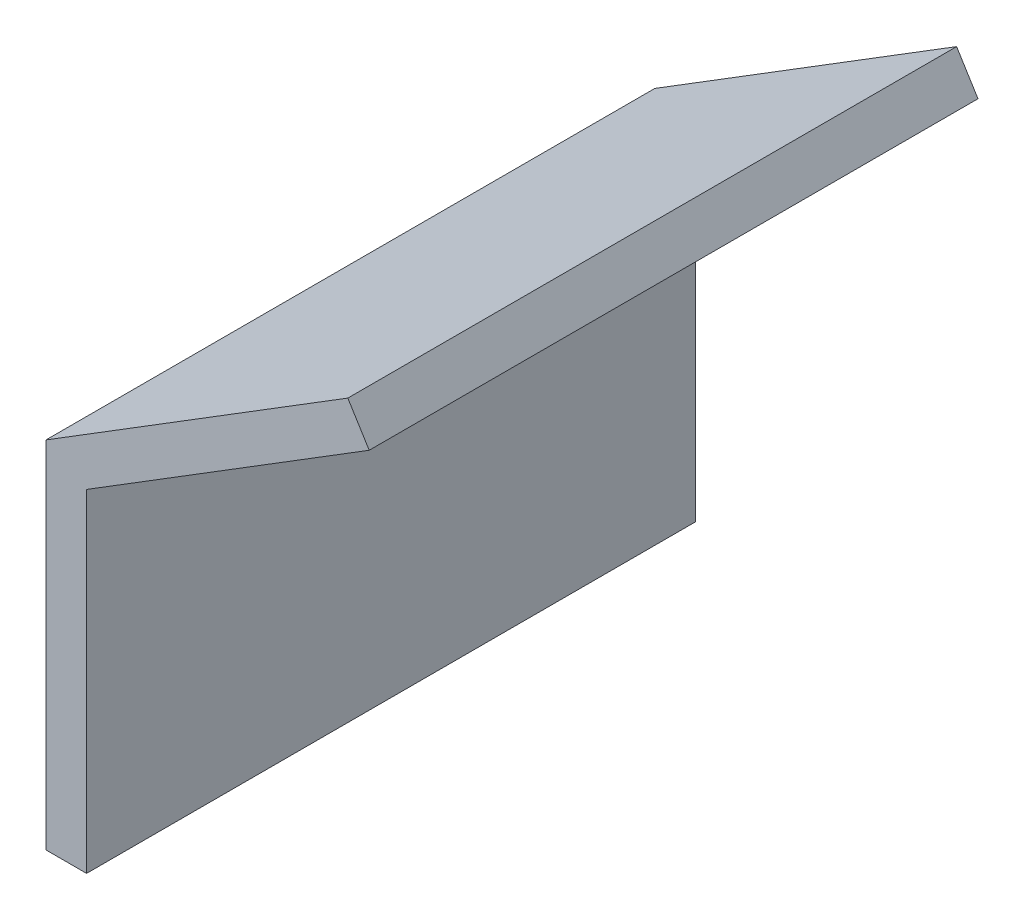
SolidWorks part; units mm, degrees
material "PLA"
ref_plane "Front Plane" through (0, 0, 0) normal (0, 0, 1) x (1, 0, 0)
ref_plane "Top Plane" through (0, 0, 0) normal (0, 1, 0) x (1, 0, 0)
ref_plane "Right Plane" through (0, 0, 0) normal (1, 0, 0) x (0, 0, -1)
sketch "Sketch1" plane through (0, 0, 0) normal (0, 0, 1) x (1, 0, 0)
  line L0 (0, 0) -> (59.4925, 36.8869)
  line L1 (0, 0) -> (0, -70)
  line L2 (8, -4.4527) -> (63.7081, 30.0878)
  line L3 (8, -4.4527) -> (8, -70)
  line L4 (59.4925, 36.8869) -> (63.7081, 30.0878)
  line L5 (0, -70) -> (8, -70)
  dimension "D1" = 70
  dimension "D2" = 70
  dimension "D3" = 121.8
  dimension "D4" = 8
extrude "Boss-Extrude1" add sketch "Sketch1" along normal mid plane 120
